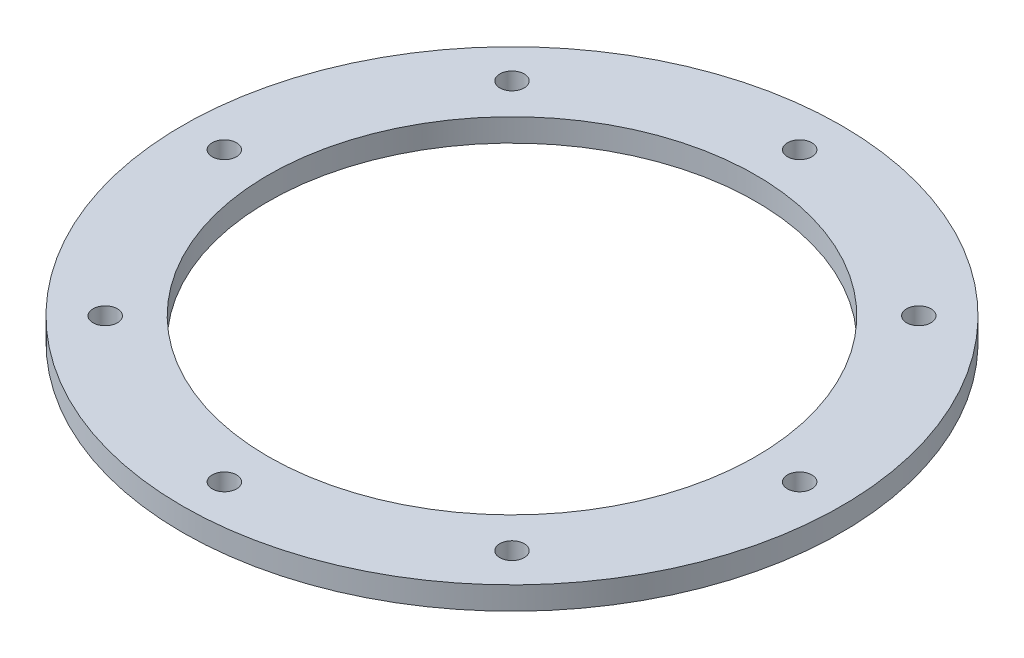
SolidWorks part; units mm, degrees
ref_plane "Front Plane" through (0, 0, 0) normal (0, 0, 1) x (1, 0, 0)
ref_plane "Top Plane" through (0, 0, 0) normal (0, 1, 0) x (1, 0, 0)
ref_plane "Right Plane" through (0, 0, 0) normal (1, 0, 0) x (0, 0, -1)
sketch "Sketch1" plane through (0, 0, 0) normal (0, 1, 0) x (1, 0, 0)
  circle A0 centre (0, 0) radius 32
  circle A1 centre (0, 0) radius 43.25
  circle A2 centre (0, 0) radius 37.75 construction
  circle A3 centre (0, 37.75) radius 1.6
  circle A4 centre (26.6933, 26.6933) radius 1.6
  circle A5 centre (37.75, 0) radius 1.6
  circle A6 centre (26.6933, -26.6933) radius 1.6
  circle A7 centre (0, -37.75) radius 1.6
  circle A8 centre (-26.6933, -26.6933) radius 1.6
  circle A9 centre (-37.75, 0) radius 1.6
  circle A10 centre (-26.6933, 26.6933) radius 1.6
  circle A11 centre (0, 0) radius 45.25 construction
  point P23 (0, 0)
  dimension "D1" = 64
  dimension "D2" = 86.5
  dimension "D3" = 3.2
  dimension "D5" = 90.5
  dimension "D6" = 7.5
  dimension "D4" = 8
extrude "Boss-Extrude1" add sketch "Sketch1" along normal blind 3
